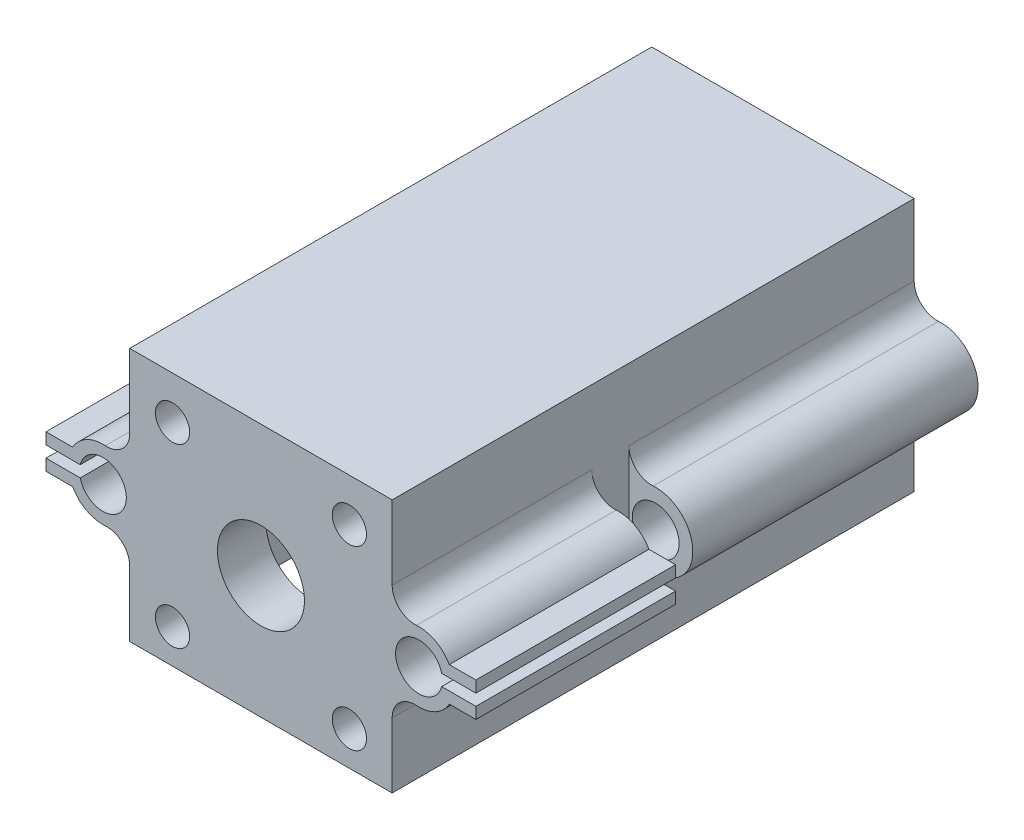
SolidWorks part; units mm, degrees
ref_plane "Alzado" through (0, 0, 0) normal (0, 0, 1) x (1, 0, 0)
ref_plane "Planta" through (0, 0, 0) normal (0, 1, 0) x (1, 0, 0)
ref_plane "Vista lateral" through (0, 0, 0) normal (1, 0, 0) x (0, 0, -1)
sketch "Croquis2" plane through (0, 0, -84) normal (0, 0, 1) x (1, 0, 0)
  line L1 (-21.5, -21.5) -> (21.5, -21.5)
  line L2 (-21.5, -21.5) -> (-21.5, 21.5)
  line L3 (-21.5, 21.5) -> (21.5, 21.5)
  line L4 (21.5, -21.5) -> (21.5, 21.5)
  line L5 (-21.5, -21.5) -> (21.5, 21.5) construction
  line L6 (-21.5, 21.5) -> (21.5, -21.5) construction
  circle A0 centre (-15.5111, 15.5111) radius 1.6
  circle A1 centre (15.5111, 15.5111) radius 1.6
  circle A2 centre (15.5111, -15.5111) radius 1.6
  circle A3 centre (-15.5111, -15.5111) radius 1.6
  point P0 (0, 0)
  dimension "D3" = 3.2
  dimension "D1" = 43
  dimension "D2" = 43
extrude "Saliente-Extruir2" add sketch "Croquis2" along normal blind 2.5
sketch "Croquis4" plane through (0, 21.5, 0) normal (0, 1, 0) x (1, 0, 0)
  line L0 (-21.5, 84) -> (-21.5, 122)
  line L1 (-21.5, 81.5) -> (-21.5, 84) construction
  line L2 (21.5, 84) -> (-21.5, 84) construction
  line L3 (21.5, 84) -> (21.5, 122)
  line L4 (21.5, 81.5) -> (21.5, 84) construction
  line L5 (21.5, 122) -> (-21.5, 122)
  line L6 (-21.5, 84) -> (21.5, 84) construction
  line L7 (21.5, 84) -> (21.5, 39)
  line L8 (21.5, 39) -> (-21.5, 39)
  line L9 (-21.5, 39) -> (-21.5, 84)
  dimension "D1" = 38
  dimension "D2" = 45
extrude "Saliente-Extruir3" add sketch "Croquis4" along normal blind 1.5
sketch "Croquis5" plane through (-21.5, 0, 0) normal (-1, 0, 0) x (0, 0, 1)
  line L1 (-122, 21.5) -> (-84, 21.5) construction
  line L2 (-84, 21.5) -> (-84, -21.5) construction
  line L4 (-81.5, 21.5) -> (-81.5, -21.5) construction
  line L6 (-81.5, 21.5) -> (-39, 21.5) construction
  line L7 (-60.25, 21.5) -> (-39, 21.5)
  line L8 (-39, 23) -> (-39, 21.5) construction
  line L9 (-39, 21.5) -> (-39, 23)
  line L10 (-122, 23) -> (-39, 23) construction
  line L11 (-39, 23) -> (-122, 23)
  line L12 (-122, 23) -> (-122, 21.5)
  line L14 (-84, -21.5) -> (-81.5, -21.5)
  line L15 (-81.5, -21.5) -> (-84, -21.5) construction
  line L16 (-81.5, -21.5) -> (-81.5, 0)
  line L17 (-60.25, 21.5) -> (-81.5, 21.5)
  line L18 (-81.5, 21.5) -> (-81.5, 0)
  line L19 (-122, 21.5) -> (-122, -21.5)
  line L20 (-122, -21.5) -> (-84, -21.5)
extrude "Saliente-Extruir4" add sketch "Croquis5" along normal blind 1.5
sketch "Croquis6" plane through (21.5, 0, 0) normal (1, 0, 0) x (0, 0, -1)
  line L1 (122, 21.5) -> (122, -21.5)
  line L3 (64, 21.5) -> (81.5, 21.5)
  line L4 (39, 21.5) -> (81.5, 21.5) construction
  line L5 (81.5, 21.5) -> (81.5, 0)
  line L6 (122, -21.5) -> (84, -21.5)
  line L8 (84, -21.5) -> (84, 21.5)
  line L9 (84, 21.5) -> (122, 21.5)
  line L10 (122, 21.5) -> (122, 23)
  line L11 (122, 23) -> (39, 23)
  line L12 (39, 23) -> (39, 21.5)
  line L13 (39, 21.5) -> (81.5, 21.5)
  line L14 (81.5, 21.5) -> (81.5, -21.5)
  line L15 (81.5, -21.5) -> (84, -21.5)
  line L18 (122, 21.5) -> (122, 23)
  line L19 (122, 23) -> (39, 23)
  line L20 (39, 23) -> (39, 21.5)
  line L21 (39, 21.5) -> (64, 21.5)
  line L22 (81.5, 0) -> (81.5, -21.5)
  line L23 (81.5, -21.5) -> (84, -21.5)
  dimension "D1" = 0
extrude "Saliente-Extruir5" add sketch "Croquis6" along normal blind 1.5
sketch "Croquis7" plane through (0, 23, 0) normal (0, 1, 0) x (1, 0, 0)
  line L0 (-23, 39) -> (-23, 30.5)
  line L1 (-23, 81.5) -> (-23, 39) construction
  line L2 (-23, 39) -> (23, 39) construction
  line L3 (-23, 30.5) -> (23, 30.5)
  line L4 (23, 30.5) -> (23, 39)
  line L5 (-23, 39) -> (23, 39)
  dimension "D1" = 8.5
extrude "Saliente-Extruir6" add sketch "Croquis7" against normal blind 44.5
sketch "Croquis8" plane through (0, 0, -39) normal (0, 0, -1) x (-1, 0, 0)
  circle A0 centre (0, 0) radius 7.625
  dimension "D1" = 15.25
extrude "Cortar-Extruir1" cut sketch "Croquis8" against normal through all
sketch "Croquis9" plane through (0, 0, -30.5) normal (0, 0, 1) x (1, 0, 0)
  line L0 (-15.5, 15.5) -> (-15.5, -15.5) construction
  line L1 (-15.5, -15.5) -> (15.5, -15.5) construction
  line L2 (15.5, -15.5) -> (15.5, 15.5) construction
  line L3 (15.5, 15.5) -> (-15.5, 15.5) construction
  circle A0 centre (-15.5, 15.5) radius 3
  circle A1 centre (15.5, 15.5) radius 3
  circle A2 centre (-15.5, -15.5) radius 3
  circle A3 centre (15.5, -15.5) radius 3
  dimension "D1" = 6
extrude "Cortar-Extruir3" cut sketch "Croquis9" against normal blind 16.5
sketch "Croquis10" plane through (-23, 0, 0) normal (-1, 0, 0) x (0, 0, 1)
  line L1 (-81.5, -21.5) -> (-81.5, 21.5) construction
  line L2 (-39, -21.5) -> (-39, 21.5) construction
  line L3 (-39, -21.5) -> (-39, 21.5)
  line L4 (-39, 21.5) -> (-81.5, 21.5)
  line L5 (-81.5, 21.5) -> (-39, 21.5) construction
  line L6 (-81.5, 21.5) -> (-81.5, 0)
  line L7 (-81.5, 0) -> (-81.5, -21.5)
  line L8 (-81.5, -21.5) -> (-39, -21.5)
extrude "Saliente-Extruir8" add sketch "Croquis10" against normal blind 1.5
sketch "Croquis11" plane through (23, 0, 0) normal (1, 0, 0) x (0, 0, -1)
  line L3 (39, 21.5) -> (81.5, 21.5) construction
  line L4 (39, -21.5) -> (39, 21.5) construction
  line L5 (39, 21.5) -> (81.5, 21.5)
  line L6 (81.5, 21.5) -> (81.5, -21.5) construction
  line L7 (81.5, 21.5) -> (81.5, 0)
  line L9 (81.5, -21.5) -> (81.5, 0)
  line L10 (39, 21.5) -> (39, -21.5)
  line L11 (39, -21.5) -> (81.5, -21.5)
extrude "Saliente-Extruir9" add sketch "Croquis11" against normal blind 1.5
sketch "Croquis12" plane through (0, 0, -81.5) normal (0, 0, 1) x (1, 0, 0)
  circle A0 centre (0, 0) radius 12.25
  dimension "D1" = 24.5
extrude "Cut-Extrude1" cut sketch "Croquis12" against normal blind 10
sketch "Sketch2" plane through (0, 0, -30.5) normal (0, 0, 1) x (1, 0, 0)
  line L0 (0, 0) -> (0, 28.1288) construction
  line L1 (-27.7, 0) -> (27.7, 0) construction
  line L2 (-23, -21.5) -> (-23, 23) construction
  line L3 (-27.7, 0) -> (-42.063, 0) construction
  line L4 (-37.6762, 1) -> (-37.6762, 3)
  line L5 (-37.6762, 1) -> (-31.6762, 1)
  line L6 (-37.6762, -1) -> (-31.6762, -1)
  line L7 (-37.6762, -1) -> (-37.6762, -3)
  line L8 (-37.6762, -3) -> (-33.0113, -3)
  line L9 (-37.6762, 3) -> (-33.0113, 3)
  line L10 (-23, 3.8884) -> (-23, -3.8884)
  line L11 (23, 3.8884) -> (23, -3.8884)
  line L12 (37.6762, 3) -> (33.0113, 3)
  line L13 (37.6762, -3) -> (33.0113, -3)
  line L14 (37.6762, -1) -> (37.6762, -3)
  line L15 (37.6762, -1) -> (31.6762, -1)
  line L16 (37.6762, 1) -> (31.6762, 1)
  line L17 (37.6762, 1) -> (37.6762, 3)
  arc A0 (-31.6762, -1) -> (-31.6762, 1) centre (-27.7, 0) ccw
  arc A1 (-33.0113, -3) -> (-23, -3.8884) centre (-27.7, 0) ccw
  arc A2 (-23, 3.8884) -> (-33.0113, 3) centre (-27.7, 0) ccw
  arc A3 (23, 3.8884) -> (33.0113, 3) centre (27.7, 0) cw
  arc A4 (33.0113, -3) -> (23, -3.8884) centre (27.7, 0) cw
  arc A5 (31.6762, -1) -> (31.6762, 1) centre (27.7, 0) cw
  dimension "D1" = 8.2
  dimension "D3" = 2
  dimension "D2" = 4.7
  dimension "D4" = 2
  dimension "D5" = 6
  dimension "D6" = 2
extrude "Boss-Extrude1" add sketch "Sketch2" against normal blind 35
sketch "Sketch3" plane through (0, 0, -122) normal (0, 0, -1) x (-1, 0, 0)
  line L0 (0, 0) -> (0, 34.345) construction
  line L1 (-23, 4.49) -> (-23, -4.49)
  line L2 (23, 4.49) -> (23, -4.49)
  line L3 (23, -3.8884) -> (23, 3.8884) construction
  line L4 (-23, -21.5) -> (-23, 23) construction
  line L5 (23, 23) -> (23, -21.5) construction
  circle A0 centre (-27.7, 0) radius 4.1
  arc A1 (-23, 4.49) -> (-23, -4.49) centre (-27.7, 0) ccw
  circle A2 centre (27.7, 0) radius 4.1
  arc A3 (23, -4.49) -> (23, 4.49) centre (27.7, 0) ccw
  line M5 (23, -21.5) -> (23, 23)
  line M7 (-23, 23) -> (-23, -21.5)
  dimension "D1" = 13
  dimension "D2" = 13
extrude "Boss-Extrude2" add sketch "Sketch3" against normal blind 50 contours A1 A0 M7 | A3 A2 M5
sketch "Sketch4" plane through (0, 0, -122) normal (0, 0, -1) x (-1, 0, 0)
  circle A0 centre (-27.7, 0) radius 4.1
  circle A1 centre (27.7, 0) radius 4.1
extrude "Boss-Extrude3" add sketch "Sketch4" against normal blind 3
fillet "Fillet1" radius 4 8 edges at (23, 4.49, -97) (23, -4.49, -97) (23, 3.8884, -48) (23, -3.8884, -48) (-23, -4.49, -97) (-23, 4.49, -97) (-23, 3.8884, -48) (-23, -3.8884, -48)
equation "\"Tornillos_NEMA_17\"= 3.2mm"
equation "\"D3@Croquis2\"=\"Tornillos_NEMA_17\""
